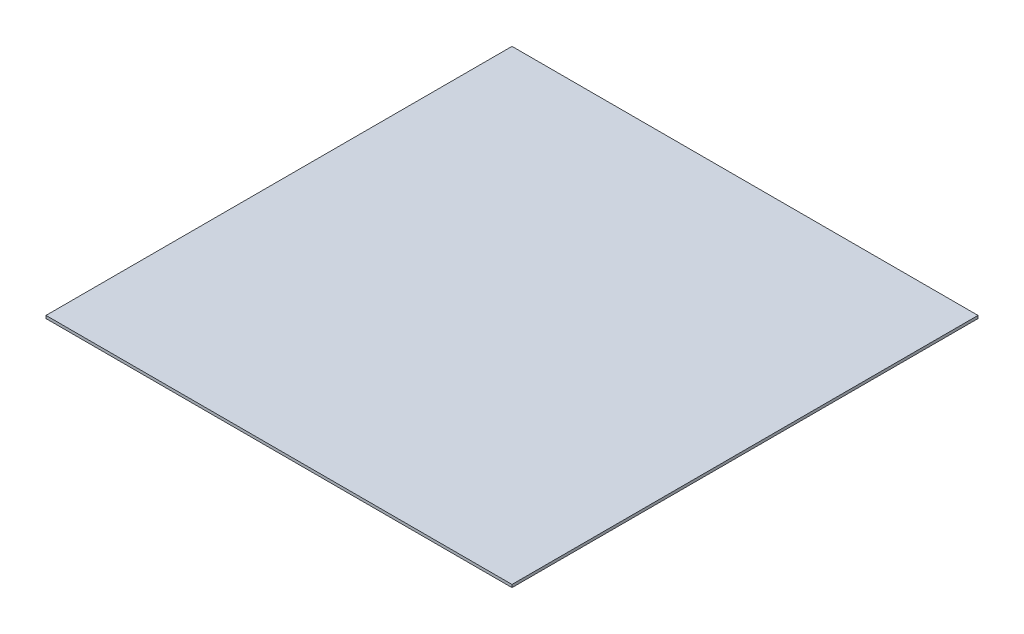
SolidWorks part; units mm, degrees
material "99.5% Aluminum Oxide"
ref_plane "Front Plane" through (0, 0, 0) normal (0, 0, 1) x (1, 0, 0)
ref_plane "Top Plane" through (0, 0, 0) normal (0, 1, 0) x (1, 0, 0)
ref_plane "Right Plane" through (0, 0, 0) normal (1, 0, 0) x (0, 0, -1)
sketch "Sketch1" plane through (0, 0, 0) normal (0, 1, 0) x (1, 0, 0)
  line L1 (-125, -125) -> (125, -125)
  line L2 (-125, -125) -> (-125, 125)
  line L3 (-125, 125) -> (125, 125)
  line L4 (125, -125) -> (125, 125)
  line L5 (-125, -125) -> (125, 125) construction
  line L6 (-125, 125) -> (125, -125) construction
  point P0 (0, 0)
  dimension "D1" = 250
extrude "Boss-Extrude1" add sketch "Sketch1" along normal mid plane 1.5
